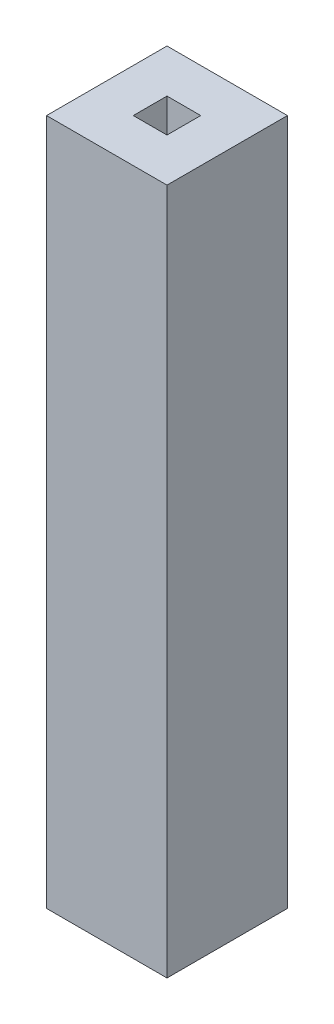
SolidWorks part; units mm, degrees
ref_plane "Front Plane" through (0, 0, 0) normal (0, 0, 1) x (1, 0, 0)
ref_plane "Top Plane" through (0, 0, 0) normal (0, 1, 0) x (1, 0, 0)
ref_plane "Right Plane" through (0, 0, 0) normal (1, 0, 0) x (0, 0, -1)
sketch "Sketch1" plane through (0, 0, 0) normal (0, 1, 0) x (1, 0, 0)
  line L1 (-1.25, 1.25) -> (1.25, 1.25)
  line L2 (-1.25, 1.25) -> (-1.25, -1.25)
  line L3 (-1.25, -1.25) -> (1.25, -1.25)
  line L4 (1.25, 1.25) -> (1.25, -1.25)
  line L5 (-1.25, 1.25) -> (1.25, -1.25) construction
  line L6 (-1.25, -1.25) -> (1.25, 1.25) construction
  point P0 (0, 0)
extrude "Extrude-Thin1" add sketch "Sketch1" along normal blind 14.25 thin
